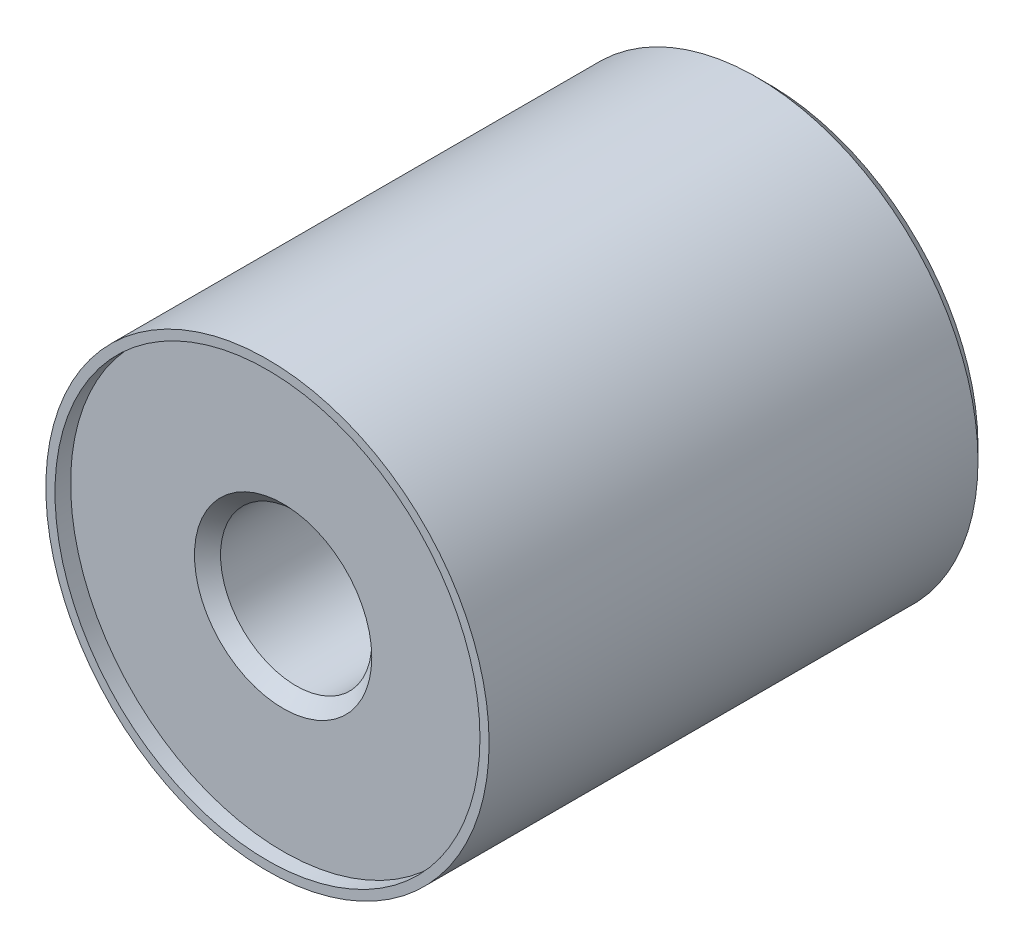
SolidWorks part; units mm, degrees
ref_plane "Front" through (0, 0, 0) normal (0, 0, 1) x (1, 0, 0)
ref_plane "Top" through (0, 0, 0) normal (0, 1, 0) x (1, 0, 0)
ref_plane "Right" through (0, 0, 0) normal (1, 0, 0) x (0, 0, -1)
sketch "Skizze1" plane through (0, 0, 0) normal (0, 0, 1) x (1, 0, 0)
  circle A0 centre (0, 0) radius 2.9
  circle A1 centre (0, 0) radius 8.5
  dimension "D1" = 5.8
  dimension "D2" = 17
extrude "Aufsatz-Linear austragen1" add sketch "Skizze1" along normal blind 18.65
sketch "Skizze2" plane through (0, 0, 18.65) normal (0, 0, 1) x (1, 0, 0)
  circle A0 centre (0, 0) radius 8.5
  circle A1 centre (0, 0) radius 8.5 construction
  circle A2 centre (0, 0) radius 8.15
  dimension "D1" = 16.3
extrude "Aufsatz-Linear austragen2" add sketch "Skizze2" along normal blind 0.6
chamfer "Fase1" distance 0.5 angle 45 3 edges at (2.9, 0, 0) (8.5, 0, 0) (2.9, 0, 18.65)
